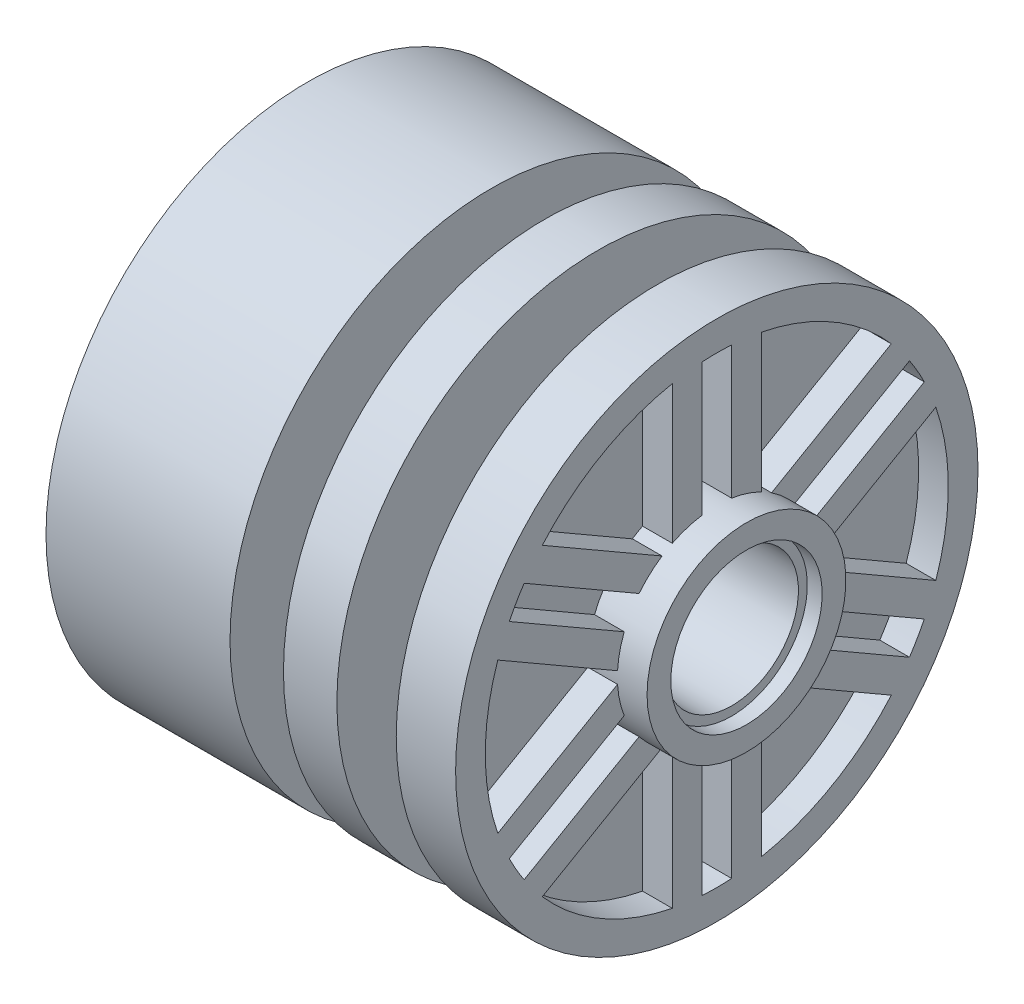
SolidWorks part; units mm, degrees
ref_plane "Front Plane" through (0, 0, 0) normal (0, 0, 1) x (1, 0, 0)
ref_plane "Top Plane" through (0, 0, 0) normal (0, 1, 0) x (1, 0, 0)
ref_plane "Right Plane" through (0, 0, 0) normal (1, 0, 0) x (0, 0, -1)
sketch "Sketch1" plane through (0, 0, 0) normal (0, 0, 1) x (1, 0, 0)
  line L0 (0, 3.35) -> (15.8, 3.35) construction
  line L1 (0, 3.35) -> (6.3, 3.35)
  line L2 (0, 3.35) -> (0, 2.55)
  line L3 (0, 2.55) -> (0.5, 2.55)
  line L4 (6.3, 3.35) -> (6.3, 7.8)
  line L5 (6.3, 7.8) -> (1, 7.8)
  line L6 (1, 7.8) -> (1, 8.8)
  line L7 (1, 8.8) -> (7.2, 8.8)
  line L8 (7.2, 8.8) -> (7.2, 5.5)
  line L9 (7.2, 5.5) -> (9, 5.5)
  line L10 (9, 5.5) -> (9, 8.8)
  line L11 (9, 8.8) -> (10.8, 8.8)
  line L12 (10.8, 8.8) -> (10.8, 5.5)
  line L13 (10.8, 5.5) -> (12.8, 5.5)
  line L14 (12.8, 5.5) -> (12.8, 8.8)
  line L15 (12.8, 8.8) -> (14.8, 8.8)
  line L16 (14.8, 8.8) -> (14.8, 7.8)
  line L17 (14.8, 7.8) -> (13.8, 7.8)
  line L18 (13.8, 7.8) -> (13.8, 3.35)
  line L19 (13.8, 3.35) -> (15.8, 3.35) construction
  line L20 (15.8, 3.35) -> (15.8, 2.55)
  line L21 (15.8, 2.55) -> (15.3, 2.55)
  line L22 (15.3, 2.55) -> (15.3, 2.25)
  line L23 (0.5, 2.55) -> (0.5, 2.25)
  line L24 (15.3, 2.25) -> (0.5, 2.25)
  line L25 (15.8, 3.35) -> (13.8, 3.35)
  line L26 (13.8, 3.35) -> (15.8, 3.35)
  line L27 (0, 0) -> (20.7545, 0) construction
  dimension "D1" = 15.8
  dimension "D2" = 3.35
  dimension "D3" = 6.3
  dimension "D4" = 0.8
  dimension "D5" = 0.5
  dimension "D6" = 7.8
  dimension "D7" = 5.3
  dimension "D8" = 1
  dimension "D9" = 6.2
  dimension "D10" = 5.5
  dimension "D11" = 1.8
  dimension "D12" = 1.8
  dimension "D13" = 2
  dimension "D14" = 2
  dimension "D15" = 1
  dimension "D16" = 3.35
  dimension "D17" = 1
  dimension "D18" = 0.8
  dimension "D19" = 2.25
  dimension "D20" = 0.5
revolve "Revolve1" add sketch "Sketch1" angle 360 about L27
sketch "Sketch2" plane through (13.8, 0, 0) normal (1, 0, 0) x (0, 0, -1)
  line L0 (-1.5, 7.6544) -> (-1.5, 2.9954)
  line L1 (-0.5, 7.784) -> (-0.5, 3.3125)
  line L2 (0.5, 7.784) -> (0.5, 3.3125)
  line L3 (1.5, 7.6544) -> (1.5, 2.9954)
  circle A0 centre (0, 0) radius 7.8 construction
  circle A1 centre (0, 0) radius 7.8 construction
  arc A2 (-1.5, 7.6544) -> (-0.5, 7.784) centre (0, 0) cw
  arc A3 (0.5, 7.784) -> (1.5, 7.6544) centre (0, 0) cw
  circle A4 centre (0, 0) radius 3.35 construction
  arc A5 (-0.5, 3.3125) -> (0.5, 3.3125) centre (0, 0) cw construction
  arc A6 (-1.5, 2.9954) -> (-0.5, 3.3125) centre (0, 0) cw
  arc A7 (0.5, 3.3125) -> (1.5, 2.9954) centre (0, 0) cw
  circle A8 centre (0, 0) radius 7.8 construction
  point P11 (0, 3.35)
  circle M7 centre (0, 0) radius 3.35
  circle M8 centre (0, 0) radius 7.8
  dimension "D1" = 1
  dimension "D2" = 1
  dimension "D3" = 1
extrude "Boss-Extrude2" add sketch "Sketch2" along normal blind 1 contours L3 L2 M8 M7 | L1 L0 M8 M7
pattern_circular "CirPattern1" count 6 over 360 about axis through (0, 0, 0) along (1, 0, 0) of "Boss-Extrude2"
ref_plane "Plane1" through (0, 5.5, 0) normal (0, 1, 0) x (1, 0, 0)
sketch "Sketch3" plane through (0, 5.5, 0) normal (0, 1, 0) x (1, 0, 0)
  line L0 (9, 5.5) -> (9, -5.5) construction
  line L1 (9, 5.5) -> (9, -5.5) construction
  line L2 (7.2, -5.5) -> (7.2, 5.5) construction
  line L3 (7.2, -5.5) -> (7.2, 5.5) construction
  line L4 (7.2, 3.6) -> (7.2, -3.6)
  line L5 (9, 3.6) -> (9, -3.6)
  line L6 (9, 3.6) -> (7.2, 3.6)
  line L7 (9, -3.6) -> (7.2, -3.6)
  point P7 (7.2, 0)
  point P10 (9, 0)
  dimension "D1" = 7.2
extrude "Cut-Extrude1" cut sketch "Sketch3" against normal through all
sketch "Sketch4" plane through (6.3, 0, 0) normal (-1, 0, 0) x (0, 0, 1)
  line L0 (0, 3.35) -> (0, 7.8) construction
  circle A0 centre (0, 0) radius 3.35 construction
  circle A1 centre (0, 0) radius 3.35 construction
  circle A2 centre (0, 0) radius 7.8 construction
  circle A3 centre (0, 6) radius 1.2
  dimension "D1" = 2.4
  dimension "D2" = 1.8
extrude "Cut-Extrude2" cut sketch "Sketch4" against normal blind 0.4
pattern_circular "CirPattern2" count 6 over 360 about axis through (0, 0, 0) along (1, 0, 0) of "Cut-Extrude2"
